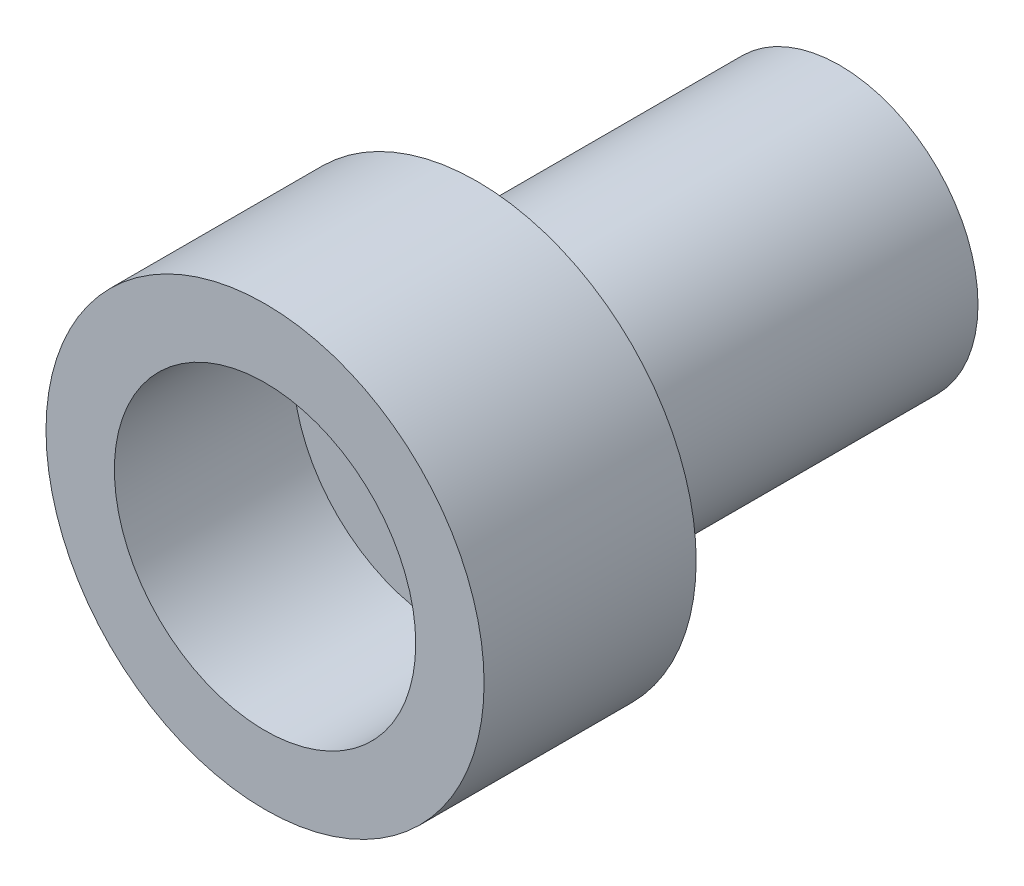
SolidWorks part; units mm, degrees
ref_plane "Alzado" through (0, 0, 0) normal (0, 0, 1) x (1, 0, 0)
ref_plane "Planta" through (0, 0, 0) normal (0, 1, 0) x (1, 0, 0)
ref_plane "Vista lateral" through (0, 0, 0) normal (1, 0, 0) x (0, 0, -1)
sketch "Croquis1" plane through (0, 0, 0) normal (1, 0, 0) x (0, 0, -1)
  line L0 (-10.7125, 0) -> (14.6551, 0) construction
  line L1 (-3.8, 3.925) -> (0, 3.925)
  line L2 (0, 3.925) -> (0, 2.475)
  line L3 (0, 2.475) -> (6.5, 2.475)
  line L4 (6.5, 2.475) -> (6.5, 1.45)
  line L5 (6.5, 1.45) -> (-0.6, 1.45)
  line L6 (-3.8, 2.7) -> (-3.8, 3.925)
  line L7 (-3.8, 2.7) -> (-0.6, 2.7)
  line L8 (-0.6, 2.7) -> (-0.6, 1.45)
  dimension "D1" = 3.8
  dimension "D2" = 10.3
  dimension "D3" = 4.95
  dimension "D4" = 7.85
  dimension "D5" = 2.9
  dimension "D6" = 5.4
  dimension "D7" = 3.2
revolve "Revolución1" add sketch "Croquis1" angle 360 about L0
